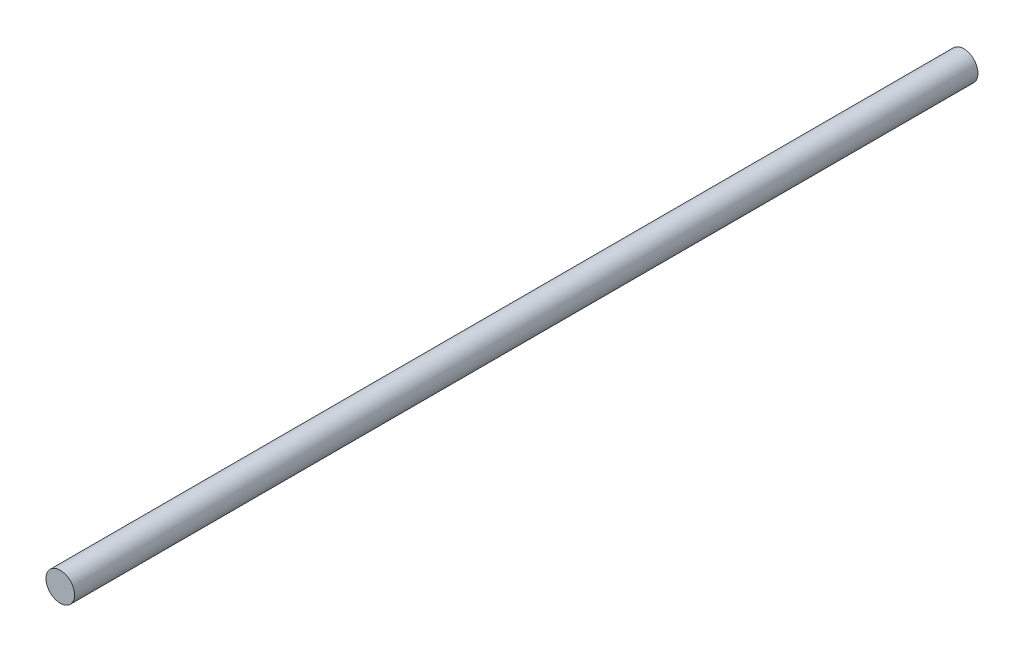
SolidWorks part; units mm, degrees
ref_plane "Alzado" through (0, 0, 0) normal (0, 0, 1) x (1, 0, 0)
ref_plane "Planta" through (0, 0, 0) normal (0, 1, 0) x (1, 0, 0)
ref_plane "Vista lateral" through (0, 0, 0) normal (1, 0, 0) x (0, 0, -1)
sketch "Croquis1" plane through (0, 0, 0) normal (0, 0, 1) x (1, 0, 0)
  circle A0 centre (0, 26) radius 4
  dimension "D1" = 8
extrude "Saliente-Extruir1" add sketch "Croquis1" against normal blind 252.5
